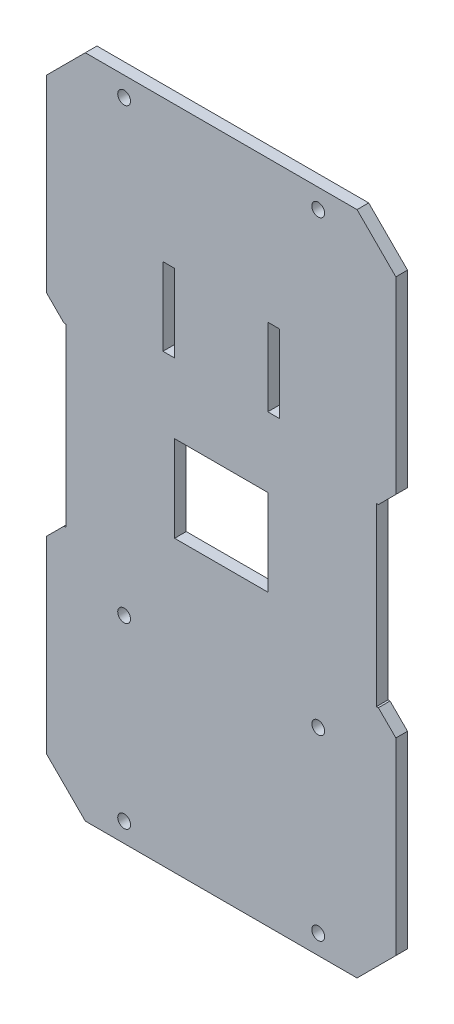
SolidWorks part; units mm, degrees
ref_plane "Front Plane" through (0, 0, 0) normal (0, 0, 1) x (1, 0, 0)
ref_plane "Top Plane" through (0, 0, 0) normal (0, 1, 0) x (1, 0, 0)
ref_plane "Right Plane" through (0, 0, 0) normal (1, 0, 0) x (0, 0, -1)
sketch "Sketch1" plane through (0, 0, 0) normal (0, 0, 1) x (1, 0, 0)
  line L0 (0.5528, 47.78) -> (20.5528, 47.78) construction
  line L1 (-49.4472, 47.78) -> (-29.4472, 47.78) construction
  line L2 (-49.4472, 47.78) -> (-49.4472, -25.43) construction
  line L3 (-49.4472, -25.43) -> (-29.4472, -25.43) construction
  line L4 (-29.4472, 47.78) -> (-29.4472, -25.43) construction
  line L5 (0.5528, 47.78) -> (0.5528, -25.43) construction
  line L6 (0.5528, -25.43) -> (20.5528, -25.43) construction
  line L7 (20.5528, 47.78) -> (20.5528, -25.43) construction
  line L8 (0.5528, -30.43) -> (20.5528, -30.43) construction
  line L9 (-49.4472, -30.43) -> (-29.4472, -30.43) construction
  line L10 (-49.4472, -30.43) -> (-49.4472, -103.64) construction
  line L11 (-49.4472, -103.64) -> (-29.4472, -103.64) construction
  line L12 (-29.4472, -30.43) -> (-29.4472, -103.64) construction
  line L13 (0.5528, -30.43) -> (0.5528, -103.64) construction
  line L14 (0.5528, -103.64) -> (20.5528, -103.64) construction
  line L15 (20.5528, -30.43) -> (20.5528, -103.64) construction
  line L16 (-59.4472, 47.78) -> (-49.4472, 57.78)
  line L17 (-49.4472, 57.78) -> (20.5528, 57.78)
  line L18 (-59.4472, 47.78) -> (-59.4472, -0.7692)
  line L19 (-49.4472, -113.64) -> (20.5528, -113.64)
  line L21 (20.5528, 57.78) -> (30.5528, 47.78)
  line L22 (30.5528, -103.64) -> (20.5528, -113.64)
  line L23 (-59.4472, -103.64) -> (-49.4472, -113.64)
  line L24 (-54.4472, 52.78) -> (-54.4472, -62.7481) construction
  line L25 (-54.4472, -50.5907) -> (-54.9472, -50.5907)
  line L26 (-54.4472, -50.5907) -> (-54.4472, -5.2692)
  line L27 (-54.4472, -5.2692) -> (-54.9472, -5.2692)
  line L29 (-59.4472, -0.7692) -> (-54.9472, -5.2692)
  line L30 (-54.9472, -50.5907) -> (-59.4472, -55.0907)
  line L31 (-59.4472, -55.0907) -> (-59.4472, -103.64)
  line L32 (-14.4472, 57.78) -> (-14.4472, -113.64) construction
  line L33 (30.5528, -55.0907) -> (30.5528, -103.64)
  line L34 (25.5528, -50.5907) -> (26.0528, -50.5907)
  line L35 (26.0528, -50.5907) -> (30.5528, -55.0907)
  line L36 (25.5528, -50.5907) -> (25.5528, -5.2692)
  line L37 (30.5528, 47.78) -> (30.5528, -0.7692)
  line L38 (30.5528, -0.7692) -> (26.0528, -5.2692)
  line L39 (25.5528, -5.2692) -> (26.0528, -5.2692)
  line L40 (-39.4472, 57.78) -> (-39.4472, 52.78) construction
  line L41 (10.5528, 57.78) -> (10.5528, 52.78) construction
  line L42 (-54.4472, -27.93) -> (25.5528, -27.93) construction
  line L43 (-29.4472, 11.175) -> (0.5528, 11.175) construction
  line L45 (-29.4472, 21.175) -> (-29.4472, 1.175)
  line L47 (-26.4472, 21.175) -> (-26.4472, 1.175)
  line L49 (0.5528, 21.175) -> (0.5528, 1.175)
  line L51 (-2.4472, 21.175) -> (-2.4472, 1.175)
  line L60 (-29.4472, 1.175) -> (-26.4472, 1.175)
  line L61 (-29.4472, 21.175) -> (-26.4472, 21.175)
  line L62 (-2.4472, 21.175) -> (0.5528, 21.175)
  line L63 (-2.4472, 1.175) -> (0.5528, 1.175)
  line L64 (-29.4472, 21.175) -> (0.5528, 21.175) construction
  line L66 (-29.4472, 1.175) -> (0.5528, 1.175) construction
  line L83 (-26.4472, -39.0454) -> (-2.4472, -39.0454)
  line L84 (-26.4472, -39.0454) -> (-26.4472, -16.8145)
  line L85 (-26.4472, -16.8145) -> (-2.4472, -16.8145)
  line L86 (-2.4472, -39.0454) -> (-2.4472, -16.8145)
  line L87 (-26.4472, -39.0454) -> (-2.4472, -16.8145) construction
  line L88 (-26.4472, -16.8145) -> (-2.4472, -39.0454) construction
  circle A0 centre (-39.4472, 52.78) radius 1.65
  circle A1 centre (10.5528, 52.78) radius 1.65
  circle A2 centre (10.5528, -108.64) radius 1.65
  circle A3 centre (-39.4472, -108.64) radius 1.65
  circle A4 centre (10.5528, -62.7481) radius 1.65
  circle A5 centre (-39.4472, -62.7481) radius 1.65
  point P16 (-59.4472, 57.78)
  point P17 (30.5528, -113.64)
  point P18 (-59.4472, -113.64)
  point P19 (30.5528, 57.78)
  point P28 (-59.4472, -27.93)
  point P35 (-59.4472, -5.2692)
  point P37 (-59.4472, -50.5907)
  point P41 (-54.6972, -50.5907)
  point P43 (25.8028, -50.5907)
  point P76 (-14.4472, -27.93)
  dimension "D17" = 3.3
  dimension "D23" = 3.3
  dimension "D28" = 3.3
  dimension "D1" = 30
  dimension "D2" = 30
  dimension "D3" = 20
  dimension "D4" = 20
  dimension "D5" = 20
  dimension "D6" = 20
  dimension "D7" = 20
  dimension "D8" = 10
  dimension "D9" = 10
  dimension "D10" = 20
  dimension "D11" = 73.21
  dimension "D12" = 73.21
  dimension "D13" = 73.21
  dimension "D14" = 73.21
  dimension "D15" = 5
  dimension "D16" = 10
  dimension "D18" = 20
  dimension "D24" = 10
  dimension "D29" = 30
  dimension "D25" = 10
extrude "Boss-Extrude2" add sketch "Sketch1" along normal blind 3
